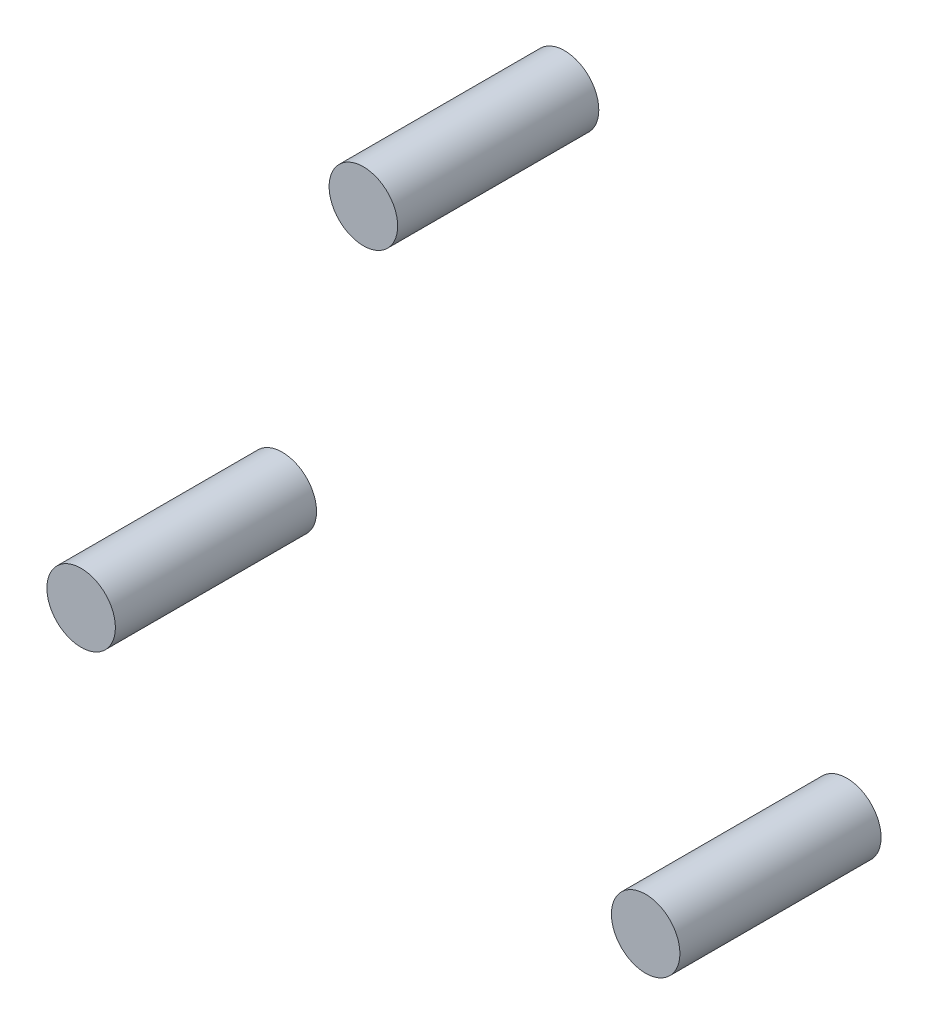
SolidWorks part; units mm, degrees
ref_plane "Front Plane" through (0, 0, 0) normal (0, 0, 1) x (1, 0, 0)
ref_plane "Top Plane" through (0, 0, 0) normal (0, 1, 0) x (1, 0, 0)
ref_plane "Right Plane" through (0, 0, 0) normal (1, 0, 0) x (0, 0, -1)
sketch "Sketch2" plane through (0, 0, 0) normal (0, 0, 1) x (1, 0, 0)
  circle A0 centre (-4.4903, -2.5925) radius 0.545
  circle A1 centre (0, 5.185) radius 0.545
  circle A2 centre (4.4903, -2.5925) radius 0.545
  point P10 (0, 0)
  dimension "D1" = 3
extrude "Boss-Extrude1" add sketch "Sketch2" along normal up to surface (3.2 mm away)
